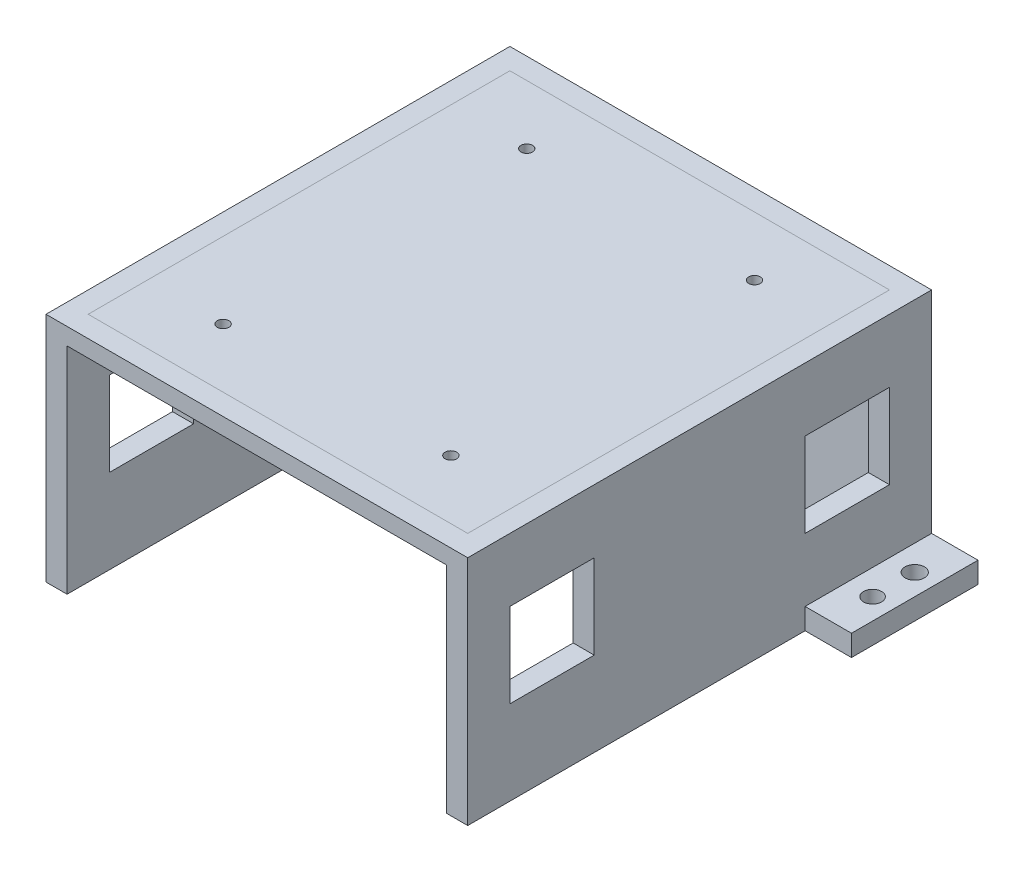
SolidWorks part; units mm, degrees
other "Markup1"
sketch "Sketch9" plane through (61, 4, 55) normal (0.4895, 0.7468, 0.4502) x (0.6843, -0.0091, -0.7291)
sketch "Sketch10" plane through (61, 4, 55) normal (0.4895, 0.7468, 0.4502) x (0.6843, -0.0091, -0.7291)
ref_plane "Front Plane" through (0, 0, 0) normal (0, 0, 1) x (1, 0, 0)
ref_plane "Top Plane" through (0, 0, 0) normal (0, 1, 0) x (1, 0, 0)
ref_plane "Right Plane" through (0, 0, 0) normal (1, 0, 0) x (0, 0, -1)
sketch "Sketch1" plane through (0, 0, 0) normal (0, 1, 0) x (1, 0, 0)
  line L1 (-45, 50) -> (45, 50)
  line L2 (-45, 50) -> (-45, -50)
  line L3 (-45, -50) -> (45, -50)
  line L4 (45, 50) -> (45, -50)
  line L5 (-45, 50) -> (45, -50) construction
  line L6 (-45, -50) -> (45, 50) construction
  point P0 (0, 0)
  dimension "D1" = 100
  dimension "D2" = 90
extrude "Boss-Extrude1" add sketch "Sketch1" along normal blind 4
sketch "Sketch2" plane through (0, 4, 0) normal (0, 1, 0) x (1, 0, 0)
  line L0 (0, -55) -> (0, 55) construction
  line L1 (-55, 0) -> (55, 0) construction
  circle A0 centre (-27, 36) radius 1.375
  circle A1 centre (27, 36) radius 1.375
  circle A2 centre (27, -36) radius 1.375
  circle A3 centre (-27, -36) radius 1.375
  dimension "D3" = 2.75
  dimension "D1" = 27
  dimension "D2" = 36
extrude "Cut-Extrude1" cut sketch "Sketch2" against normal blind 4
sketch "Sketch3" plane through (0, 4, 0) normal (0, 1, 0) x (1, 0, 0)
  line L5 (-45, 50) -> (45, 50)
  line L6 (-45, 50) -> (-45, -50)
  line L7 (-45, -50) -> (45, -50)
  line L8 (50, -55) -> (50, 55)
  line L9 (50, 55) -> (-50, 55)
  line L10 (-50, 55) -> (-50, -55)
  line L11 (-50, -55) -> (50, -55)
  line L12 (50, -55) -> (50, 55)
  line L13 (50, 55) -> (-50, 55)
  line L14 (-50, 55) -> (-50, -55)
  line L15 (-50, -55) -> (50, -55)
  line L16 (45, 50) -> (45, -50)
  dimension "D1" = 5
extrude "Boss-Extrude2" add sketch "Sketch3" against normal blind 55 separate body
sketch "Sketch4" plane through (0, -51, 0) normal (0, -1, 0) x (1, 0, 0)
  line L0 (0, -55) -> (0, 55) construction
  line L1 (-50, -55) -> (-61, -55)
  line L2 (-50, -55) -> (-50, -25)
  line L3 (-50, -25) -> (-61, -25)
  line L4 (-61, -55) -> (-61, -25)
  dimension "D1" = 30
  dimension "D2" = 61
extrude "Boss-Extrude3" add sketch "Sketch4" against normal blind 5
mirror "Mirror1" about plane through (0, 0, 0) normal (1, 0, 0) of "Boss-Extrude3"
sketch "Sketch5" plane through (0, -51, 0) normal (0, -1, 0) x (1, 0, 0)
  line L0 (-61, -25) -> (-61, -55) construction
  line L1 (61, -55) -> (-61, -55) construction
  line L2 (0, -55) -> (0, 55) construction
  circle A0 centre (-56, -45) radius 2.2866
  circle A1 centre (-56, -35) radius 2.1499
  circle A2 centre (56, -45) radius 2.2866
  circle A3 centre (56, -35) radius 2.1499
  dimension "D1" = 10
  dimension "D2" = 5
  dimension "D3" = 10
extrude "Cut-Extrude2" cut sketch "Sketch5" against normal through all
sketch "Sketch6" plane through (0, 0, 55) normal (0, 0, 1) x (1, 0, 0)
  line L0 (55, 0) -> (-55, 0) construction
  line L1 (-45, 0) -> (45, 0)
  line L2 (-45, 0) -> (-45, -51)
  line L3 (-45, -51) -> (45, -51)
  line L4 (45, 0) -> (45, -51)
  line L7 (-50, -51) -> (-50, 4) construction
  dimension "D1" = 5
extrude "Cut-Extrude3" cut sketch "Sketch6" against normal blind 10
sketch "Sketch7" plane through (-50, 0, 0) normal (-1, 0, 0) x (0, 0, 1)
  line L0 (-55, -46) -> (-55, 4) construction
  line L1 (-45, -11) -> (-25, -11)
  line L2 (-45, -11) -> (-45, -31)
  line L3 (-45, -31) -> (-25, -31)
  line L4 (-25, -11) -> (-25, -31)
  line L5 (-45, -11) -> (-25, -31) construction
  line L6 (-45, -31) -> (-25, -11) construction
  line L7 (-55, 4) -> (55, 4) construction
  line L8 (0, -55) -> (0, 55) construction
  line L9 (45, -31) -> (25, -31)
  line L10 (25, -11) -> (25, -31)
  line L11 (45, -11) -> (25, -11)
  line L12 (45, -11) -> (45, -31)
  point P0 (-35, -21)
  dimension "D1" = 20
  dimension "D2" = 25
  dimension "D3" = 20
  dimension "D4" = 20
extrude "Cut-Extrude4" cut sketch "Sketch7" against normal through all
sketch "Sketch8" plane through (0, 0, -55) normal (0, 0, -1) x (-1, 0, 0)
  line L0 (0, 30.25) -> (0, -30.25) construction
  line L1 (-20, -38.5) -> (20, -38.5)
  line L2 (-20, -38.5) -> (-20, -23.5)
  line L3 (-20, -23.5) -> (20, -23.5)
  line L4 (20, -38.5) -> (20, -23.5)
  line L5 (-20, -38.5) -> (20, -23.5) construction
  line L6 (-20, -23.5) -> (20, -38.5) construction
  line L7 (-61, -46) -> (-50, -46) construction
  point P0 (0, -31)
  dimension "D1" = 40
  dimension "D2" = 15
  dimension "D3" = 15
extrude "Cut-Extrude5" cut sketch "Sketch8" against normal through all
